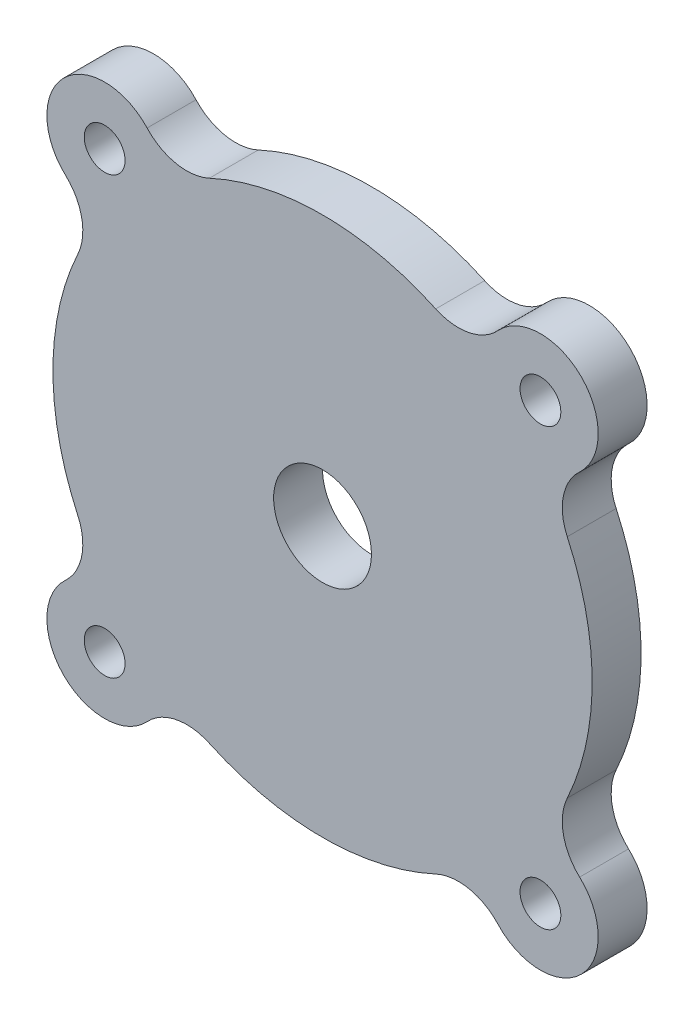
SolidWorks part; units mm, degrees
material "6061 Alloy"
ref_plane "Front Plane" through (0, 0, 0) normal (0, 0, 1) x (1, 0, 0)
ref_plane "Top Plane" through (0, 0, 0) normal (0, 1, 0) x (1, 0, 0)
ref_plane "Right Plane" through (0, 0, 0) normal (1, 0, 0) x (0, 0, -1)
sketch "Sketch1" plane through (0, 0, 0) normal (0, 0, 1) x (1, 0, 0)
  line L1 (-28.2843, -28.2843) -> (28.2843, -28.2843) construction
  line L2 (-28.2843, -28.2843) -> (-28.2843, 28.2843) construction
  line L3 (-28.2843, 28.2843) -> (28.2843, 28.2843) construction
  line L4 (28.2843, -28.2843) -> (28.2843, 28.2843) construction
  line L5 (-28.2843, -28.2843) -> (28.2843, 28.2843) construction
  line L6 (-28.2843, 28.2843) -> (28.2843, -28.2843) construction
  circle A0 centre (0, 0) radius 40 construction
  arc A1 (-20.7853, 28.1597) -> (-28.1597, 20.7853) centre (-28.2843, 28.2843) ccw
  arc A2 (20.7853, 28.1597) -> (28.1597, 20.7853) centre (28.2843, 28.2843) ccw construction
  arc A3 (20.7853, -28.1597) -> (28.1597, -20.7853) centre (28.2843, -28.2843) ccw
  arc A4 (-20.7853, -28.1597) -> (-28.1597, -20.7853) centre (-28.2843, -28.2843) ccw construction
  arc A5 (28.1597, -20.7853) -> (20.7853, -28.1597) centre (28.2843, -28.2843) ccw construction
  arc A6 (-28.1597, -20.7853) -> (-20.7853, -28.1597) centre (-28.2843, -28.2843) ccw
  arc A7 (-28.1597, 20.7853) -> (-20.7853, 28.1597) centre (-28.2843, 28.2843) ccw construction
  arc A8 (28.1597, 20.7853) -> (20.7853, 28.1597) centre (28.2843, 28.2843) ccw
  arc A9 (-20.7853, 28.1597) -> (20.7853, 28.1597) centre (0, 0) cw
  arc A10 (28.1597, 20.7853) -> (28.1597, -20.7853) centre (0, 0) cw
  arc A11 (20.7853, -28.1597) -> (-20.7853, -28.1597) centre (0, 0) cw
  arc A12 (-28.1597, -20.7853) -> (-28.1597, 20.7853) centre (0, 0) cw
  dimension "D1" = 80
  dimension "D2" = 15
  dimension "D3" = 70
extrude "Boss-Extrude1" add sketch "Sketch1" along normal mid plane 6.35
fillet "Fillet1" radius 7 8 edges at (-28.1597, 20.7853, 0) (-28.1597, -20.7853, 0) (-20.7853, -28.1597, 0) (20.7853, -28.1597, 0) (28.1597, -20.7853, 0) (28.1597, 20.7853, 0) (20.7853, 28.1597, 0) (-20.7853, 28.1597, 0)
hole_wizard "M5 Clearance Hole1" positions "Sketch3" profile "Sketch2" hole size "M5" standard "ANSI Metric"
sketch "Sketch3" plane through (0, 0, 3.175) normal (0, 0, 1) x (1, 0, 0)
  point P0 (-28.2843, 28.2843)
  point P3 (28.2843, 28.2843)
  point P6 (28.2843, -28.2843)
  point P9 (-28.2843, -28.2843)
sketch "Sketch2" plane through (-28.2843, 28.2843, 3.175) normal (1, 0, 0) x (0, -1, 0)
  line L0 (0, 0) -> (0, 7.9423)
  line L1 (0, 7.9423) -> (2.65, 6.35)
  line L2 (2.65, 6.35) -> (2.65, 0)
  line L5 (2.65, 0) -> (0, 0)
  line L10 (0, 7.9423) -> (-2.65, 6.35) construction
  line L11 (0, -6.35) -> (0, 107.95) construction
  dimension "Hole Dia." = 5.3
  dimension "Hole Depth" = 6.35
  dimension "Drill Angle" = 118
sketch "Sketch4" plane through (0, 0, 3.175) normal (0, 0, 1) x (1, 0, 0)
  circle A0 centre (0, 0) radius 6.35
  dimension "D1" = 12.7
extrude "Cut-Extrude1" cut sketch "Sketch4" against normal through all
